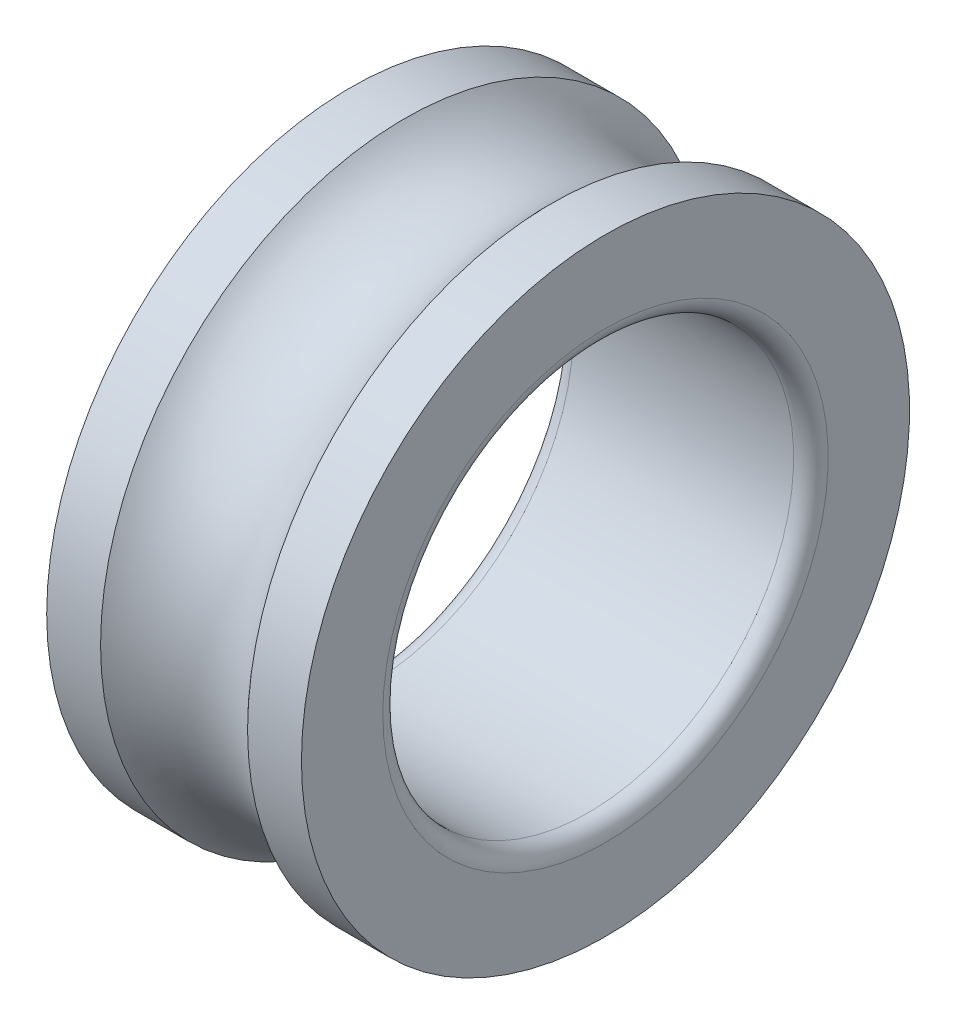
SolidWorks part; units mm, degrees
ref_plane "Front Plane" through (0, 0, 0) normal (0, 0, 1) x (1, 0, 0)
ref_plane "Top Plane" through (0, 0, 0) normal (0, 1, 0) x (1, 0, 0)
ref_plane "Right Plane" through (0, 0, 0) normal (1, 0, 0) x (0, 0, -1)
sketch "Sketch1" plane through (0, 0, 0) normal (0, 0, 1) x (1, 0, 0)
  line L0 (0, 0) -> (6465.2406, 0) construction
  line L1 (4.4721, 18.5) -> (7.75, 18.5)
  line L2 (-7.75, 18.5) -> (-4.4721, 18.5)
  line L3 (-7.75, 18.5) -> (-7.75, 13.55)
  line L4 (-6.7, 12.5) -> (6.7, 12.5)
  line L5 (7.75, 18.5) -> (7.75, 13.55)
  line L6 (-7.75, 18.5) -> (7.75, 12.5) construction
  line L7 (-7.75, 12.5) -> (7.75, 18.5) construction
  arc A0 (-4.4721, 18.5) -> (4.4721, 18.5) centre (0, 22.5) ccw
  arc A1 (6.7, 12.5) -> (7.75, 13.55) centre (6.7, 13.55) ccw
  arc A2 (-7.75, 13.55) -> (-6.7, 12.5) centre (-6.7, 13.55) ccw
  point P3 (0, 15.5)
  dimension "D4" = 12
  dimension "D6" = 1.05
  dimension "D1" = 15.5
  dimension "D2" = 12.5
  dimension "D3" = 18.5
  dimension "D5" = 4
revolve "Revolve1" add sketch "Sketch1" angle 360 about L0
